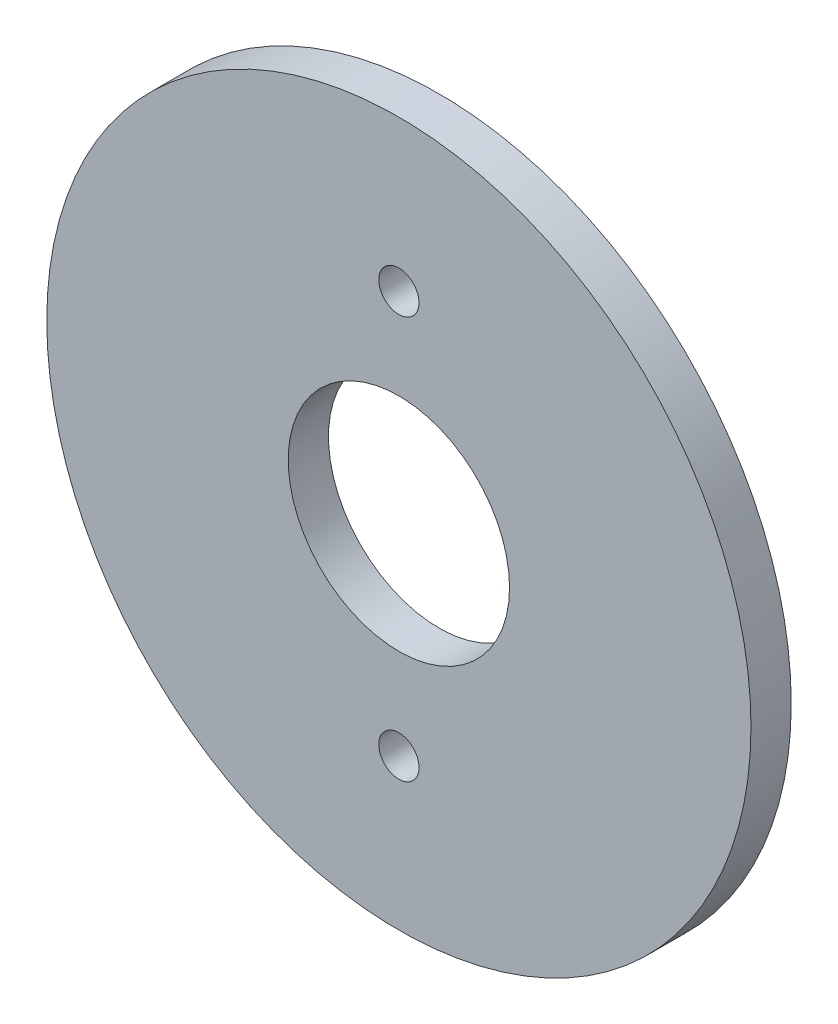
SolidWorks part; units mm, degrees
ref_plane "Спереди" through (0, 0, 0) normal (0, 0, 1) x (1, 0, 0)
ref_plane "Сверху" through (0, 0, 0) normal (0, 1, 0) x (1, 0, 0)
ref_plane "Справа" through (0, 0, 0) normal (1, 0, 0) x (0, 0, -1)
sketch "Эскиз1" plane through (0, 0, 0) normal (0, 0, 1) x (1, 0, 0)
  line L0 (0, 17.5) -> (0, -17.5) construction
  circle A0 centre (0, 0) radius 17.5
  circle A1 centre (0, 0) radius 10 construction
  circle A2 centre (0, 0) radius 5.5
  circle A3 centre (0, 10) radius 1
  circle A4 centre (0, -10) radius 1
  dimension "D1" = 35
  dimension "D2" = 20
  dimension "D3" = 11
  dimension "D4" = 2
  dimension "D5" = 2
extrude "Бобышка-Вытянуть1" add sketch "Эскиз1" along normal blind 2
